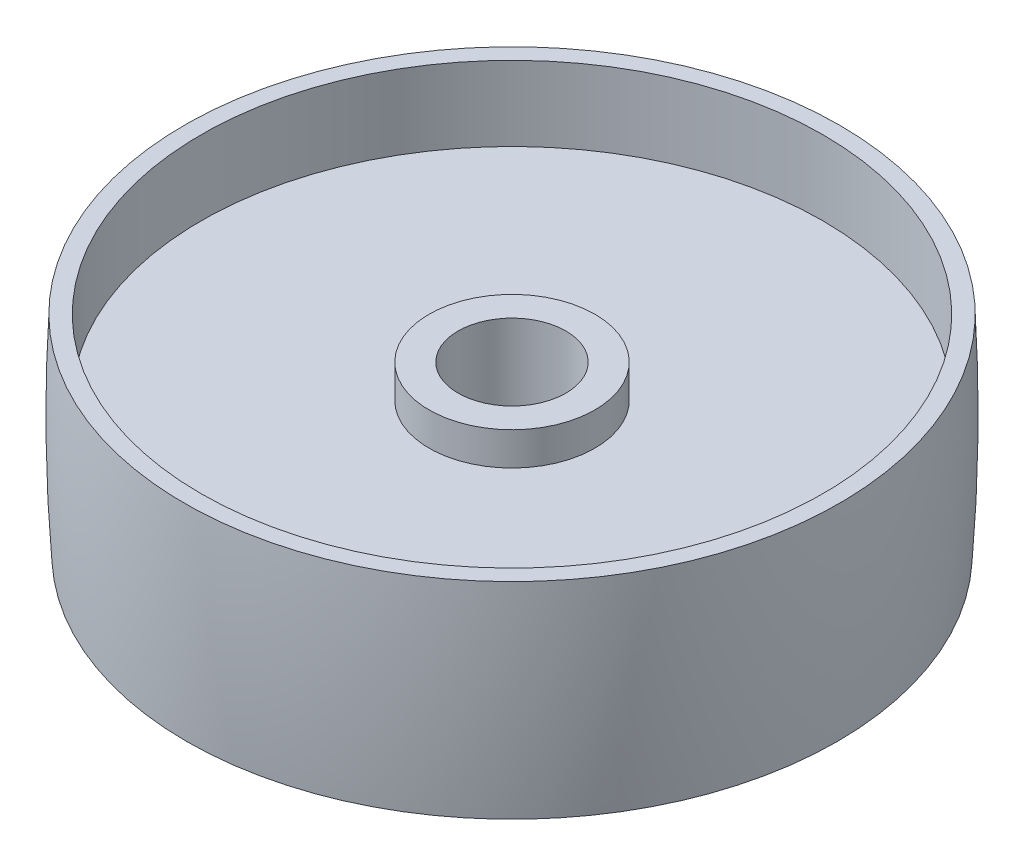
SolidWorks part; units mm, degrees
ref_plane "Plan de face" through (0, 0, 0) normal (0, 0, 1) x (1, 0, 0)
ref_plane "Plan de dessus" through (0, 0, 0) normal (0, 1, 0) x (1, 0, 0)
ref_plane "Plan de droite" through (0, 0, 0) normal (1, 0, 0) x (0, 0, -1)
sketch "Esquisse1" plane through (0, 0, 0) normal (0, 0, 1) x (1, 0, 0)
  line L0 (13, 40) -> (13, 0)
  line L1 (13, 0) -> (20, 0)
  line L2 (20, 0) -> (20, 22)
  line L3 (20, 22) -> (75, 22)
  line L4 (75, 22) -> (75, 0)
  line L5 (75, 0) -> (78.5, 0)
  line L6 (13, 40) -> (20, 40)
  line L7 (20, 40) -> (20, 32)
  line L8 (20, 32) -> (75, 32)
  line L9 (75, 32) -> (75, 50)
  line L10 (75, 50) -> (79, 50)
  line L11 (0, 0) -> (0, 21.9598) construction
  line L12 (79.5, 50) -> (79.5, -39.6108) construction
  arc A0 (79, 50) -> (78.5, 0) centre (-349.8286, 29.2858) cw
  dimension "D2" = 79
  dimension "D3" = 75
  dimension "D1" = 13
  dimension "D4" = 40
  dimension "D5" = 50
  dimension "D6" = 1
  dimension "D7" = 1
  dimension "D8" = 10
  dimension "D9" = 20
  dimension "D10" = 20
  dimension "D11" = 8
  dimension "D12" = 75
revolve "Révolution1" add sketch "Esquisse1" angle 360 about L11
